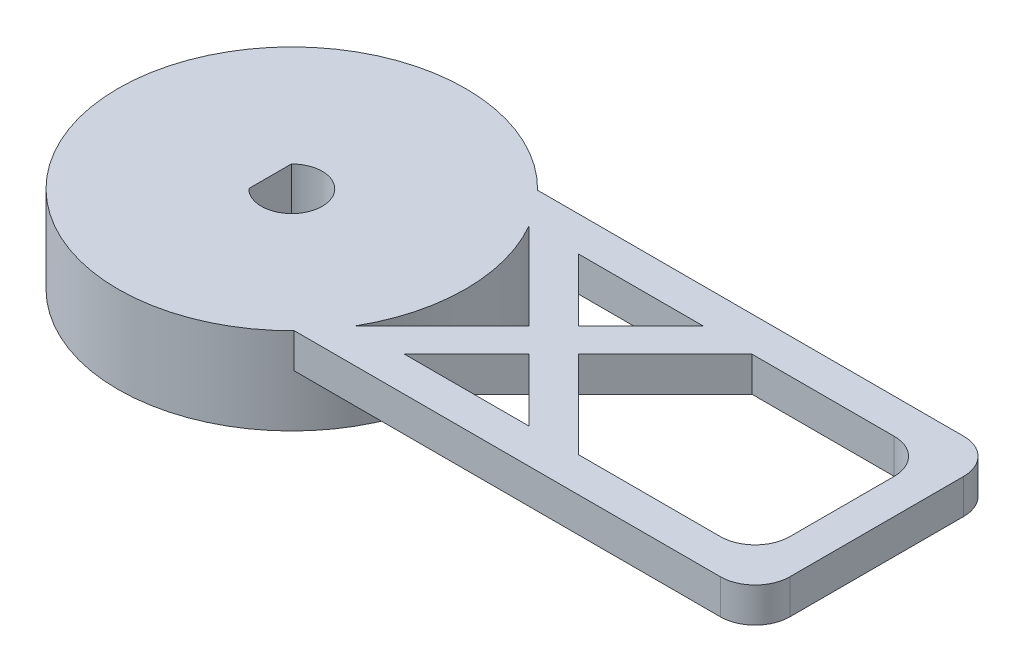
SolidWorks part; units mm, degrees
ref_plane "Front Plane" through (0, 0, 0) normal (0, 0, 1) x (1, 0, 0)
ref_plane "Top Plane" through (0, 0, 0) normal (0, 1, 0) x (1, 0, 0)
ref_plane "Right Plane" through (0, 0, 0) normal (1, 0, 0) x (0, 0, -1)
sketch "Sketch1" plane through (0, 0, 0) normal (0, 1, 0) x (1, 0, 0)
  line L0 (0, 0) -> (-1.25, 0) construction
  line L1 (-1.25, -1.2247) -> (-1.25, 1.2247)
  circle A0 centre (0, 0) radius 10
  arc A1 (-1.25, -1.2247) -> (-1.25, 1.2247) centre (0, 0) ccw
  point P7 (-1.25, 0)
  dimension "D1" = 20
  dimension "D2" = 3.5
  dimension "D3" = 1.25
extrude "Boss-Extrude1" add sketch "Sketch1" along normal blind 5
sketch "Sketch2" plane through (0, 5, 0) normal (0, 1, 0) x (1, 0, 0)
  line L0 (10, 0) -> (50.3063, 0) construction
  line L1 (8.6603, 5) -> (33.6603, 5)
  line L2 (7.1414, 7) -> (33.6603, 7)
  line L3 (33.6603, 7) -> (33.6603, 5)
  line L4 (7.1414, 7) -> (8.6603, 5)
  line L5 (7.1414, -7) -> (33.6603, -7)
  line L6 (33.6603, -7) -> (33.6603, -5)
  line L7 (8.6603, -5) -> (33.6603, -5)
  line L8 (7.1414, -7) -> (8.6603, -5)
  circle A0 centre (0, 0) radius 10 construction
  dimension "D1" = 5
  dimension "D2" = 2
  dimension "D3" = 25
extrude "Boss-Extrude2" add sketch "Sketch2" against normal blind 2
sketch "Sketch3" plane through (0, 0, 5) normal (0, 0, -1) x (-1, 0, 0)
  line L0 (-33.6603, 5) -> (-8.6603, 5) construction
  line L1 (-33.6603, 3) -> (-31.6603, 3)
  line L2 (-33.6603, 3) -> (-33.6603, 5)
  line L3 (-33.6603, 5) -> (-31.6603, 5)
  line L4 (-31.6603, 3) -> (-31.6603, 5)
  dimension "D1" = 2
extrude "Boss-Extrude3" add sketch "Sketch3" along normal up to next
sketch "Sketch4" plane through (0, 5, 0) normal (0, 1, 0) x (1, 0, 0)
  line L3 (31.6603, -5) -> (8.6603, -5) construction
  line L14 (11.4887, -5) -> (15.0745, -1.4142)
  line L15 (11.4887, 5) -> (15.0745, 1.4142)
  line L16 (18.6603, 5) -> (15.0745, 1.4142)
  line L17 (18.6603, -5) -> (15.0745, -1.4142)
  line L18 (18.6603, 5) -> (21.4887, 5)
  line L19 (18.6603, -5) -> (21.4887, -5)
  line L23 (16.4887, 0) -> (21.4887, 5)
  line L25 (16.4887, 0) -> (21.4887, -5)
  line L26 (13.6603, 0) -> (8.6603, -5)
  line L27 (13.6603, 0) -> (8.6603, 5)
  line L28 (8.6603, 5) -> (11.4887, 5)
  line L29 (8.6603, -5) -> (11.4887, -5)
extrude "Boss-Extrude5" add sketch "Sketch4" against normal blind 2
fillet "Fillet1" radius 2 4 edges at (31.6603, 4, 5) (31.6603, 4, -5) (33.6603, 4, 7) (33.6603, 4, -7)
